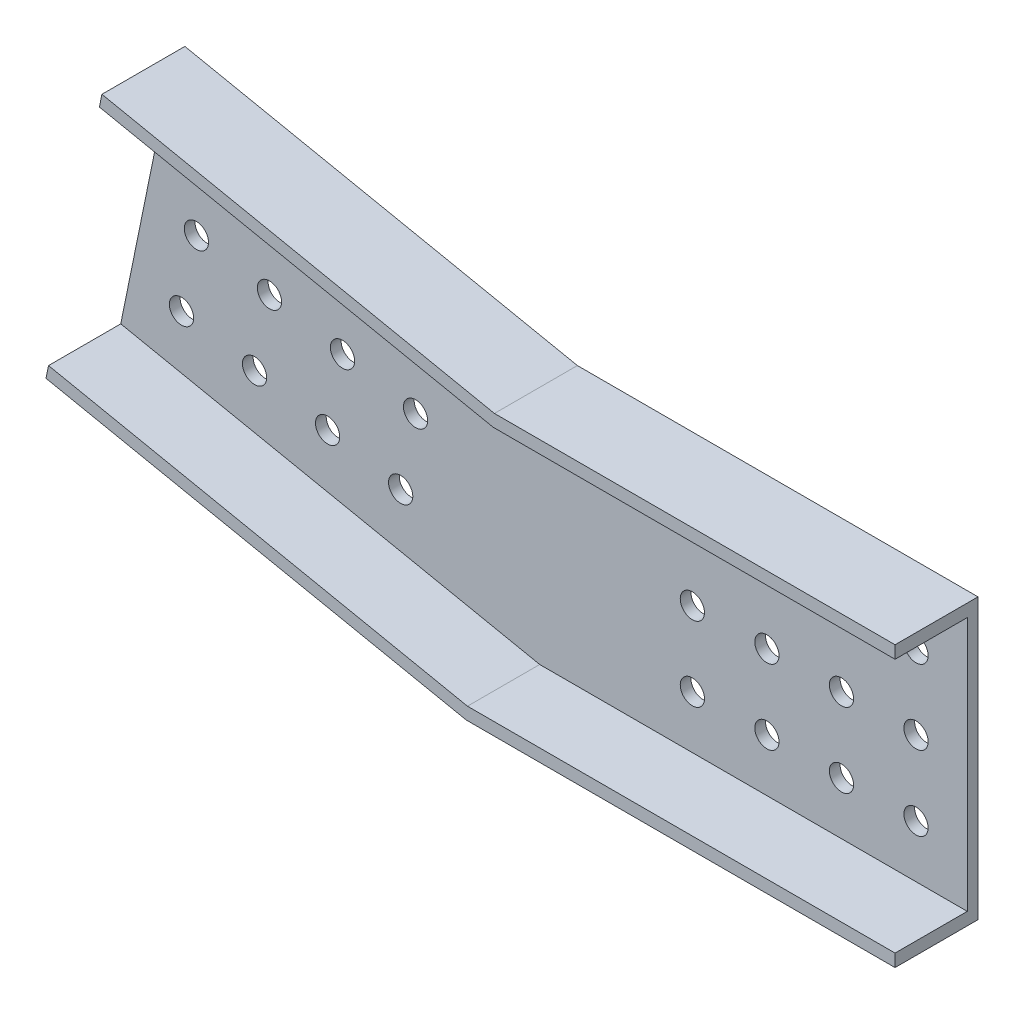
SolidWorks part; units mm, degrees
ref_plane "前视基准面" through (0, 0, 0) normal (0, 0, 1) x (1, 0, 0)
ref_plane "上视基准面" through (0, 0, 0) normal (0, 1, 0) x (1, 0, 0)
ref_plane "右视基准面" through (0, 0, 0) normal (1, 0, 0) x (0, 0, -1)
sketch "草图2" plane through (0, 0, 0) normal (0, 0, 1) x (1, 0, 0)
  line L0 (-1000, 0) -> (49000, 0) construction
  line L1 (0, 0) -> (-480, 97.9796) construction
  line L2 (-480, 97.9796) -> (-500, 0) construction
  line L3 (-500, 0) -> (0, 0) construction
  line L4 (15.1531, 150) -> (445, 150)
  line L5 (445, 150) -> (445, -150)
  line L6 (445, -150) -> (-15.1531, -150)
  line L7 (15.1531, 150) -> (-406.0092, 235.9694)
  line L8 (-406.0092, 235.9694) -> (-466.0092, -57.9694)
  line L9 (-466.0092, -57.9694) -> (-15.1531, -150)
  dimension "D1" = 100
  dimension "D2" = 500
  dimension "D3" = 300
  dimension "D4" = 445
  dimension "D5" = 300
  dimension "D6" = 445
extrude "凸台-拉伸1" add sketch "草图2" along normal blind 89
sketch "草图3" plane through (0, 0, 89) normal (0, 0, 1) x (1, 0, 0)
  line L0 (-408.7092, 222.7421) -> (13.7893, 136.5)
  line L1 (-406.0092, 235.9694) -> (-466.0092, -57.9694) construction
  line L2 (13.7893, 136.5) -> (445, 136.5)
  line L3 (445, -150) -> (445, 150) construction
  line L4 (445, 136.5) -> (445, -136.5)
  line L5 (445, -136.5) -> (-13.7893, -136.5)
  line L6 (-13.7893, -136.5) -> (-463.3092, -44.7421)
  line L7 (-463.3092, -44.7421) -> (-408.7092, 222.7421)
  line L8 (15.1531, 150) -> (-406.0092, 235.9694) construction
  line L9 (445, 150) -> (15.1531, 150) construction
  line L10 (15.1531, 150) -> (-15.1531, -150) construction
  line L11 (-466.0092, -57.9694) -> (-15.1531, -150) construction
  dimension "D1" = 13.5
  dimension "D2" = 13.5
extrude "切除-拉伸1" cut sketch "草图3" against normal blind 77.5
sketch "草图4" plane through (0, 0, 0) normal (0, 0, -1) x (-1, 0, 0)
  line L0 (-445, 150) -> (-15.1531, 150) construction
  line L1 (-445, -150) -> (-445, 150) construction
  circle A0 centre (-390, 80) radius 13
  dimension "D1" = 26
  dimension "D2" = 70
  dimension "D3" = 55
extrude "切除-拉伸2" cut sketch "草图4" against normal through all
pattern_linear "阵列(线性)1" count 4 spacing 80 along (-1, 0, 0) count 3 spacing 80 along (0, -1, 0) of "切除-拉伸2"
sketch "草图5" plane through (0, 0, 0) normal (0, 0, -1) x (-1, 0, 0)
  line L0 (-15.1531, 150) -> (406.0092, 235.9694) construction
  line L1 (406.0092, 235.9694) -> (466.0092, -57.9694) construction
  circle A0 centre (366.1204, 156.3837) radius 13
  circle A1 centre (-150, 80) radius 13 construction
  dimension "D1" = 70
  dimension "D2" = 55
extrude "切除-拉伸3" cut sketch "草图5" against normal through all
pattern_linear "阵列(线性)2" count 4 spacing 80 along (0.9798, -0.2, 0) count 3 spacing 80 along (-0.2, -0.9798, 0) of "切除-拉伸3"
